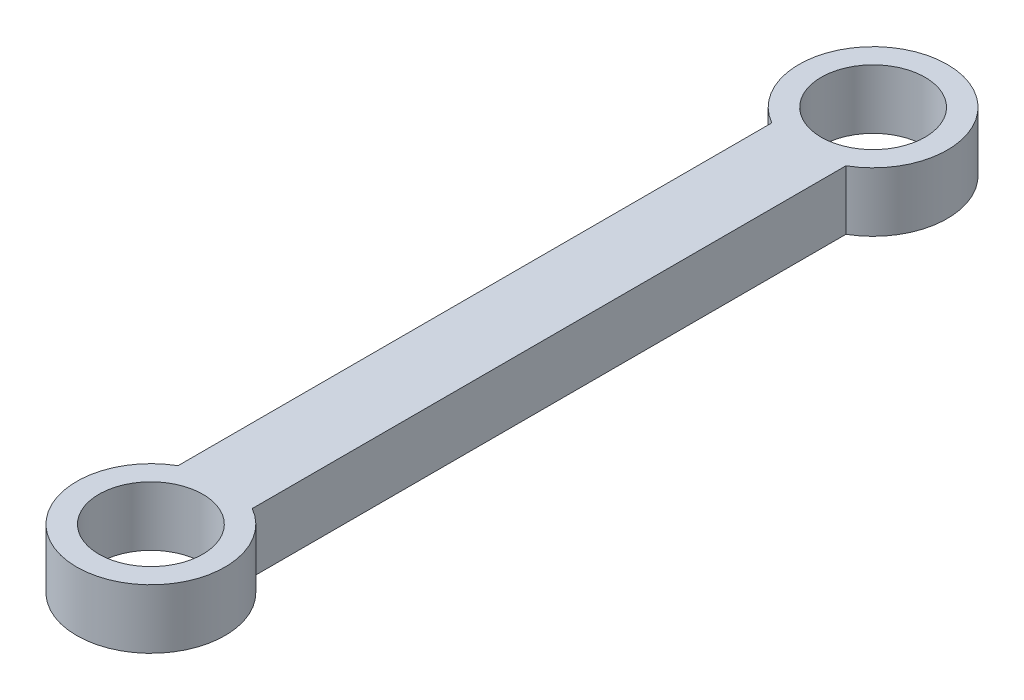
SolidWorks part; units mm, degrees
material "1023 Carbon Steel Sheet (SS)"
ref_plane "Front Plane" through (0, 0, 0) normal (0, 0, 1) x (1, 0, 0)
ref_plane "Top Plane" through (0, 0, 0) normal (0, 1, 0) x (1, 0, 0)
ref_plane "Right Plane" through (0, 0, 0) normal (1, 0, 0) x (0, 0, -1)
sketch "Sketch1" plane through (0, 0, 0) normal (0, 1, 0) x (1, 0, 0)
  line L0 (0, 0) -> (2.8684, 0) construction
  line L2 (-1.25, 10) -> (-1.25, -10)
  line L4 (1.25, 10) -> (1.25, -10)
  line L5 (-1.25, 10) -> (1.25, -10) construction
  line L6 (-1.25, -10) -> (1.25, 10) construction
  arc A0 (-1.25, -10) -> (1.25, -10) centre (0, -12.1651) ccw
  arc A1 (-1.25, 10) -> (1.25, 10) centre (0, 12.1651) cw
  circle A2 centre (0, 12.1651) radius 1.75
  circle A3 centre (0, -12.1651) radius 1.75
  point P0 (0, 0)
  dimension "D4" = 5
  dimension "D5" = 3.5
  dimension "D6" = 3.5
  dimension "D1" = 20
  dimension "D2" = 2.5
extrude "Boss-Extrude1" add sketch "Sketch1" along normal mid plane 2
